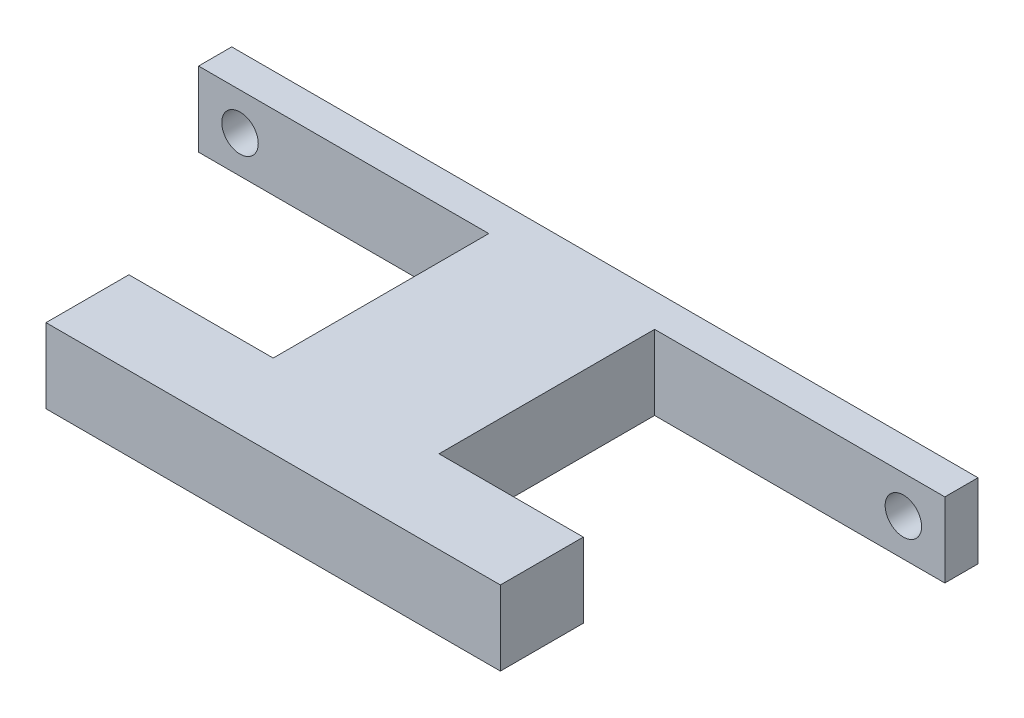
SolidWorks part; units mm, degrees
ref_plane "Front Plane" through (0, 0, 0) normal (0, 0, 1) x (1, 0, 0)
ref_plane "Top Plane" through (0, 0, 0) normal (0, 1, 0) x (1, 0, 0)
ref_plane "Right Plane" through (0, 0, 0) normal (1, 0, 0) x (0, 0, -1)
sketch "Sketch1" plane through (0, 0, 0) normal (0, 0, 1) x (1, 0, 0)
  line L3 (0, 2.54) -> (0, 16.409)
  line L4 (-57.15, 2.54) -> (-57.15, -2.54)
  line L6 (57.15, 2.54) -> (57.15, -2.54)
  line L9 (57.15, 2.54) -> (57.15, 5.715)
  line L10 (-57.15, 2.54) -> (-57.15, 5.715)
  line L11 (0, 0) -> (6.9271, 0)
  line L12 (57.15, -2.54) -> (57.15, -5.715)
  line L13 (-57.15, -2.54) -> (-57.15, -5.715)
  line L14 (-57.15, 5.715) -> (57.15, 5.715)
  line L15 (57.15, -5.715) -> (-57.15, -5.715)
  circle A0 centre (50.8, 0) radius 2.794
  circle A1 centre (-50.8, 0) radius 2.794
  point P4 (0, 0)
  dimension "D2" = 5.588
  dimension "D3" = 5.588
  dimension "D1" = 101.6
  dimension "D5" = 3.175
  dimension "D6" = 3.175
extrude "Boss-Extrude1" add sketch "Sketch1" along normal blind 5.08
sketch "Sketch2" plane through (0, 5.715, 0) normal (0, 1, 0) x (1, 0, 0)
  line L0 (-57.15, 0) -> (-57.15, -5.08)
  line L1 (-57.15, 0) -> (57.0574, 0)
  line L2 (-57.15, -5.08) -> (57.0574, -5.08)
  line L3 (57.0574, 0) -> (57.0574, -5.08)
sketch "Sketch3" plane through (0, 0, 5.08) normal (0, 0, 1) x (1, 0, 0)
  line L0 (-57.15, 5.715) -> (57.0574, 5.715) construction
  line L1 (-12.7, -5.715) -> (12.7, -5.715)
  line L2 (-12.7, -5.715) -> (-12.7, 5.715)
  line L3 (-12.7, 5.715) -> (12.7, 5.715)
  line L4 (12.7, -5.715) -> (12.7, 5.715)
  line L5 (-12.7, -5.715) -> (12.7, 5.715) construction
  line L6 (-12.7, 5.715) -> (12.7, -5.715) construction
  point P0 (0, 0)
  dimension "D1" = 25.4
extrude "Boss-Extrude2" add sketch "Sketch3" along normal blind 45.72
sketch "Sketch4" plane through (0, 0, 50.8) normal (0, 0, 1) x (1, 0, 0)
  line L0 (0, 0) -> (0, 10.3542)
  line L1 (-12.7, -5.715) -> (12.7, -5.715) construction
  line L2 (12.7, 5.715) -> (34.7967, 5.715)
  line L3 (12.7, 5.715) -> (12.7, -5.715)
  line L4 (12.7, -5.715) -> (34.7967, -5.715)
  line L5 (34.7967, 5.715) -> (34.7967, -5.715)
  line L6 (-12.7, -5.715) -> (-34.7967, -5.715)
  line L7 (-34.7967, 5.715) -> (-34.7967, -5.715)
  line L8 (-12.7, 5.715) -> (-34.7967, 5.715)
  line L9 (-12.7, 5.715) -> (-12.7, -5.715)
  line M6 (12.7, -5.715) -> (12.7, 5.715)
  line M8 (-12.7, 5.715) -> (-12.7, -5.715)
  dimension "D1" = 0
extrude "Boss-Extrude3" add sketch "Sketch4" against normal blind 12.7 contours L5 L2 L4 M6 | L8 L7 L6 M8
sketch "Sketch5" plane through (0, -5.715, 0) normal (0, -1, 0) x (1, 0, 0)
  line L0 (0, 0) -> (0, -16.8877)
